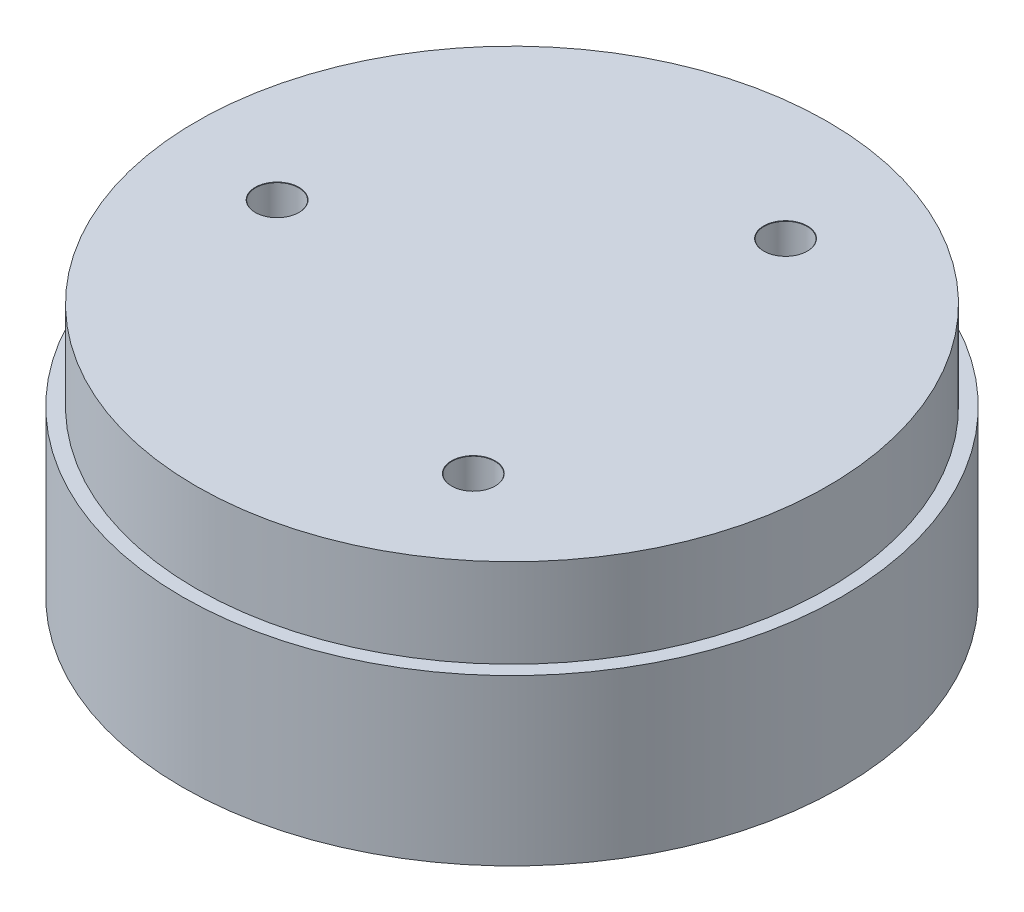
SolidWorks part; units mm, degrees
ref_plane "Front Plane" through (0, 0, 0) normal (0, 0, 1) x (1, 0, 0)
ref_plane "Top Plane" through (0, 0, 0) normal (0, 1, 0) x (1, 0, 0)
ref_plane "Right Plane" through (0, 0, 0) normal (1, 0, 0) x (0, 0, -1)
sketch "Sketch5" plane through (0, 0, 0) normal (0, 1, 0) x (-1, 0, 0)
  circle A0 centre (0, 0) radius 26
  dimension "D1" = 52
extrude "Boss-Extrude3" add sketch "Sketch5" along normal blind 13
sketch "Sketch6" plane through (0, 13, 0) normal (0, 1, 0) x (-1, 0, 0)
  circle A0 centre (0, 0) radius 24.9
  dimension "D1" = 49.8
extrude "Boss-Extrude4" add sketch "Sketch6" along normal blind 7
sketch "Sketch2" plane through (0, 20, 0) normal (0, 1, 0) x (-1, 0, 0)
  line L0 (0, 26.65) -> (0, -26.65) construction
  line L1 (-26.65, 0) -> (26.65, 0) construction
  line L2 (-6.3181, -15.2533) -> (0, 0) construction
  line L3 (-10.0507, 13.0983) -> (0, 0) construction
  line L4 (0, 0) -> (16.3688, 2.155) construction
  circle A0 centre (0, 0) radius 26.65 construction
  circle A1 centre (0, 0) radius 16.51 construction
  point P12 (-6.3181, -15.2533)
  point P13 (-10.0507, 13.0983)
  point P15 (16.3688, 2.155)
  point P23 (-10.0507, 13.0983)
  point P25 (16.3688, 2.155)
  point P27 (-6.3181, -15.2533)
  dimension "D1" = 16.51
  dimension "D2" = 53.3
  dimension "D3" = 22.5
  dimension "D4" = 120
  dimension "D5" = 120
hole_wizard "M3 Clearance Hole1" positions "Sketch2" profile "Sketch14" hole size "M3" standard "ANSI Metric" end condition through all
sketch "Sketch14" plane through (6.3181, 20, -15.2533) normal (1, 0, 0) x (0, 0, 1)
  line L0 (0, 0) -> (0, 20)
  line L1 (0, 20) -> (1.7, 20)
  line L2 (1.7, 20) -> (1.7, 0.025)
  line L3 (1.7, 0.025) -> (1.725, 0)
  line L5 (1.725, 0) -> (0, 0)
  line L6 (-1.7, 0.025) -> (-1.725, 0) construction
  line L11 (0, -6.35) -> (0, 107.95) construction
  dimension "Thru Hole Dia." = 3.4
  dimension "Thru Hole Depth" = 20
  dimension "Near C'Sink Dia." = 3.45
  dimension "Near C'Sink Angle" = 90
